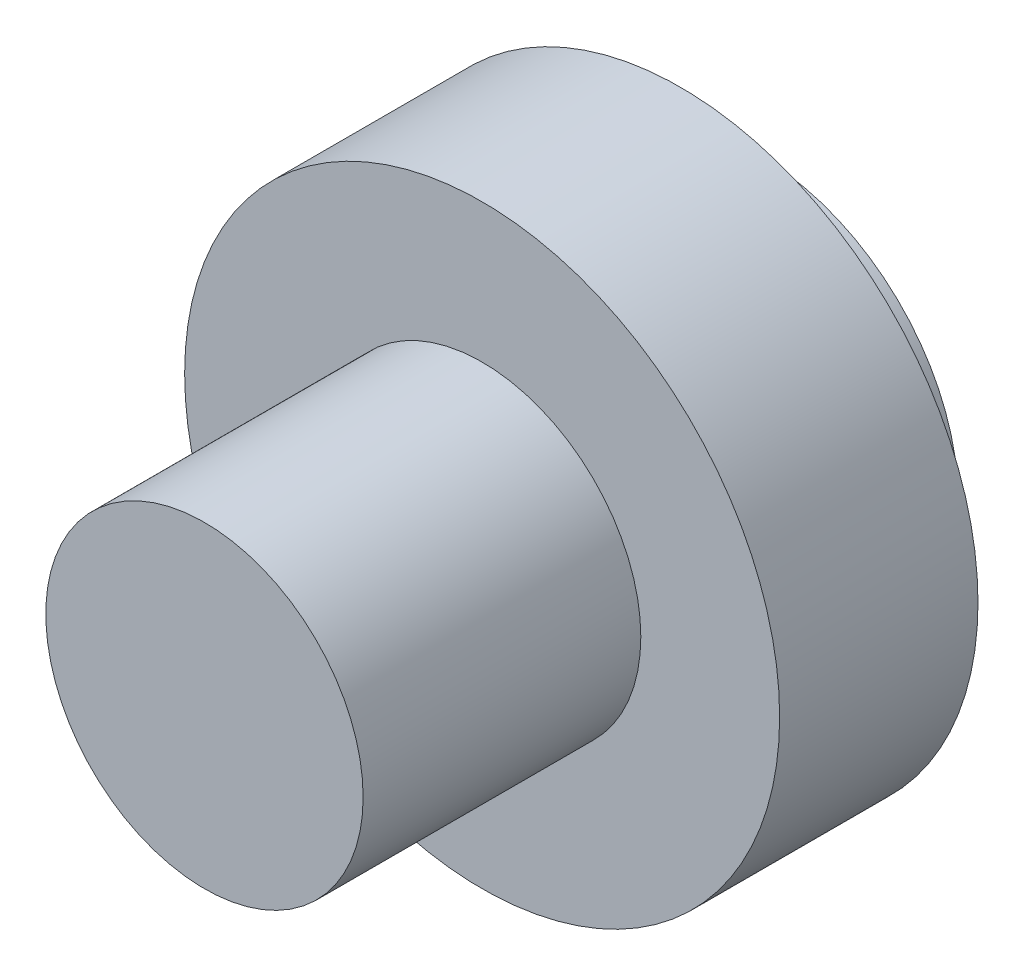
SolidWorks part; units mm, degrees
ref_plane "Piano frontale" through (0, 0, 0) normal (0, 0, 1) x (1, 0, 0)
ref_plane "Piano superiore" through (0, 0, 0) normal (0, 1, 0) x (1, 0, 0)
ref_plane "Piano destro" through (0, 0, 0) normal (1, 0, 0) x (0, 0, -1)
sketch "Schizzo1" plane through (0, 0, 0) normal (0, 0, 1) x (1, 0, 0)
  circle A0 centre (0, 0) radius 5
  dimension "D1" = 10
extrude "Estrusione-Estrusione1" add sketch "Schizzo1" along normal blind 2
sketch "Schizzo2" plane through (0, 0, 2) normal (0, 0, 1) x (1, 0, 0)
  circle A0 centre (0, 0) radius 7.5
  dimension "D1" = 15
extrude "Estrusione-Estrusione2" add sketch "Schizzo2" along normal blind 5
sketch "Schizzo3" plane through (0, 0, 7) normal (0, 0, 1) x (1, 0, 0)
  circle A0 centre (0, 0) radius 4
  dimension "D1" = 8
extrude "Estrusione-Estrusione3" add sketch "Schizzo3" along normal blind 7
